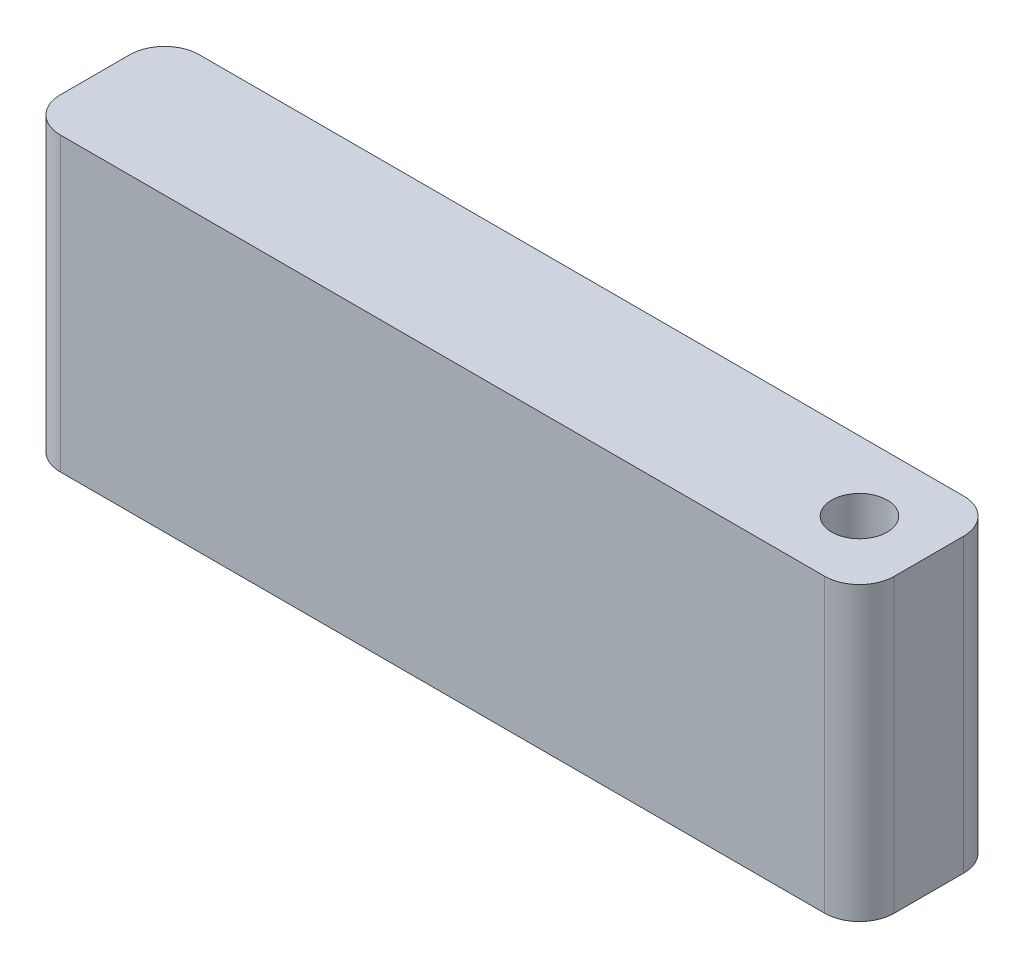
SolidWorks part; units mm, degrees
ref_plane "前视基准面" through (0, 0, 0) normal (0, 0, 1) x (1, 0, 0)
ref_plane "上视基准面" through (0, 0, 0) normal (0, 1, 0) x (1, 0, 0)
ref_plane "右视基准面" through (0, 0, 0) normal (1, 0, 0) x (0, 0, -1)
sketch "草图1" plane through (0, 0, 0) normal (0, 1, 0) x (1, 0, 0)
  line L0 (50, 0) -> (0, 0) construction
  line L1 (-55, 10) -> (55, 10)
  line L2 (-60, 5) -> (-60, -5)
  line L3 (-55, -10) -> (55, -10)
  line L4 (60, 5) -> (60, -5)
  line L5 (-60, 10) -> (60, -10) construction
  line L6 (-60, -10) -> (60, 10) construction
  circle A0 centre (50, 0) radius 4
  arc A1 (55, 10) -> (60, 5) centre (55, 5) cw
  arc A2 (60, -5) -> (55, -10) centre (55, -5) cw
  arc A3 (-55, -10) -> (-60, -5) centre (-55, -5) cw
  arc A4 (-60, 5) -> (-55, 10) centre (-55, 5) cw
  point P0 (0, 0)
  dimension "D2" = 8
  dimension "D5" = 5
  dimension "D1" = 50
  dimension "D3" = 20
  dimension "D4" = 120
extrude "凸台-拉伸1" add sketch "草图1" along normal mid plane 42
sketch "草图2" plane through (0, 0, 0) normal (0, 0, 1) x (1, 0, 0)
  line L0 (50, 21) -> (50, -21) construction
  line L1 (54, 21) -> (46, 21) construction
  line L2 (46, -21) -> (54, -21) construction
  line L3 (50, 0) -> (0, 0) construction
